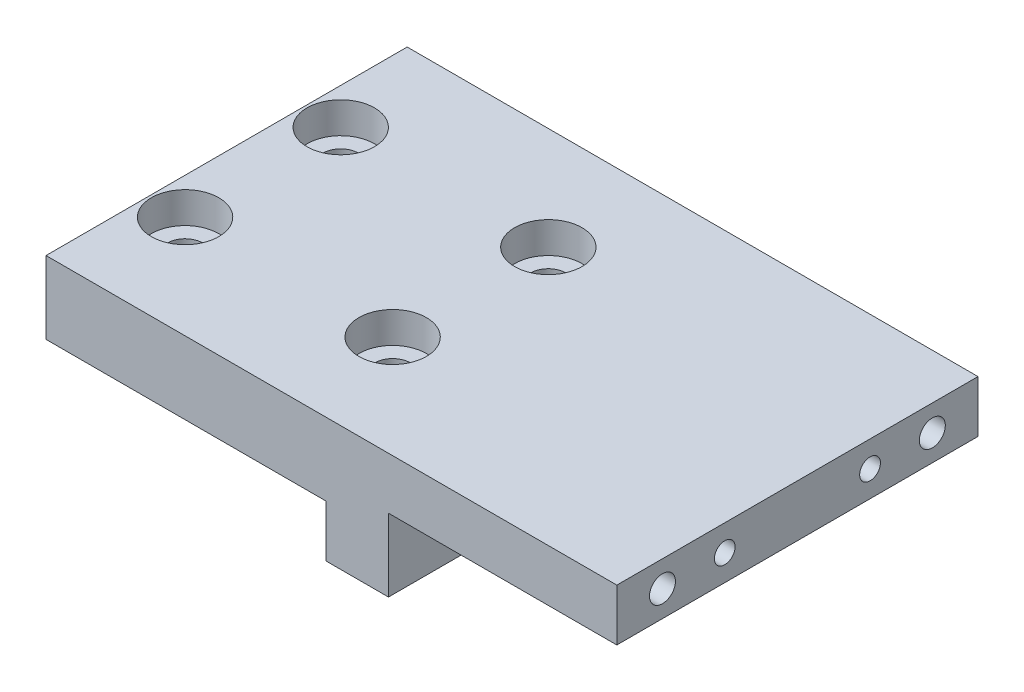
SolidWorks part; units mm, degrees
ref_plane "Front Plane" through (0, 0, 0) normal (0, 0, 1) x (1, 0, 0)
ref_plane "Top Plane" through (0, 0, 0) normal (0, 1, 0) x (1, 0, 0)
ref_plane "Right Plane" through (0, 0, 0) normal (1, 0, 0) x (0, 0, -1)
sketch "Sketch1" plane through (0, 0, 0) normal (0, 0, 1) x (1, 0, 0)
  line L0 (0, 0) -> (27, 0)
  line L1 (27, -5) -> (33, -5)
  line L2 (33, -5) -> (33, 2)
  line L3 (33, 2) -> (55, 2)
  line L4 (55, 2) -> (55, 7)
  line L5 (55, 7) -> (0, 7)
  line L6 (0, 7) -> (0, 0)
  line L7 (27, -5) -> (27, 0)
  dimension "D1" = 2
  dimension "D2" = 6
  dimension "D3" = 27
  dimension "D4" = 28
  dimension "D5" = 5
  dimension "D6" = 12
extrude "Boss-Extrude1" add sketch "Sketch1" against normal blind 34.8
ref_plane "Plane1" through (0, 0, -17.4) normal (0, 0, 1) x (1, 0, 0)
sketch "Sketch2" plane through (0, 7, 0) normal (0, 1, 0) x (1, 0, 0)
  line L0 (0, 17.4) -> (55, 17.4) construction
  line L1 (0, 34.8) -> (0, 0) construction
  line L2 (55, 34.8) -> (55, 0) construction
  line L3 (13.5, 34.8) -> (13.5, 0) construction
  line L4 (55, 34.8) -> (0, 34.8) construction
  line L5 (55, 0) -> (0, 0) construction
  circle A0 centre (3.5, 24.9) radius 1.7
  circle A1 centre (23.5, 24.9) radius 1.7
  circle A2 centre (23.5, 9.9) radius 1.7
  circle A3 centre (3.5, 9.9) radius 1.7
  dimension "D6" = 3.4
  dimension "D1" = 13.5
  dimension "D2" = 10
  dimension "D3" = 7.5
  dimension "D4" = 2
  dimension "D5" = 2
extrude "Cut-Extrude1" cut sketch "Sketch2" against normal up to next
sketch "Sketch3" plane through (33, 0, 0) normal (1, 0, 0) x (0, 0, -1)
  line L0 (17.4, -5) -> (17.4, 2) construction
  line L1 (34.8, -5) -> (0, -5) construction
  line L2 (34.8, 2) -> (0, 2) construction
  line L3 (34.8, 2) -> (0, 2) construction
  circle A0 centre (8.9, -1) radius 0.8
  circle A1 centre (25.9, -1) radius 0.8
  point P8 (0, 0)
  dimension "D1" = 1.6
  dimension "D2" = 8.5
  dimension "D3" = 3
extrude "Cut-Extrude2" cut sketch "Sketch3" against normal up to surface (6 mm away) up to face at (27, -2.5, -17.4)
sketch "Sketch4" plane through (55, 0, 0) normal (1, 0, 0) x (0, 0, -1)
  line L0 (0, 4.5) -> (34.8, 4.5) construction
  line L1 (0, 2) -> (0, 7) construction
  line L2 (34.8, 2) -> (34.8, 7) construction
  line L3 (17.4, 7) -> (17.4, 2) construction
  line L4 (34.8, 7) -> (0, 7) construction
  line L5 (34.8, 2) -> (0, 2) construction
  circle A1 centre (4.4, 4.5) radius 1.25
  circle A3 centre (30.4, 4.5) radius 1.25
  point P11 (17.4, 4.5)
  dimension "D1" = 2.5
  dimension "D4" = 13
extrude "Cut-Extrude3" cut sketch "Sketch4" against normal blind 10
sketch "Sketch5" plane through (55, 0, 0) normal (1, 0, 0) x (0, 0, -1)
  line L0 (17.4, 7) -> (17.4, 2) construction
  line L1 (34.8, 7) -> (0, 7) construction
  line L2 (34.8, 2) -> (0, 2) construction
  line L3 (0, 4.5) -> (34.8, 4.5) construction
  line L4 (0, 2) -> (0, 7) construction
  line L5 (34.8, 2) -> (34.8, 7) construction
  circle A0 centre (10.4, 4.5) radius 1
  circle A1 centre (24.4, 4.5) radius 1
  dimension "D1" = 2
  dimension "D2" = 7
extrude "Cut-Extrude4" cut sketch "Sketch5" against normal blind 4
sketch "Sketch6" plane through (0, 7, 0) normal (0, 1, 0) x (1, 0, 0)
  circle A0 centre (3.5, 24.9) radius 3.25
  circle A1 centre (23.5, 24.9) radius 3.25
  circle A2 centre (23.5, 9.9) radius 3.25
  circle A3 centre (3.5, 9.9) radius 3.25
  dimension "D1" = 6.5
  dimension "D2" = 2
  dimension "D3" = 2
extrude "Cut-Extrude5" cut sketch "Sketch6" against normal blind 3
